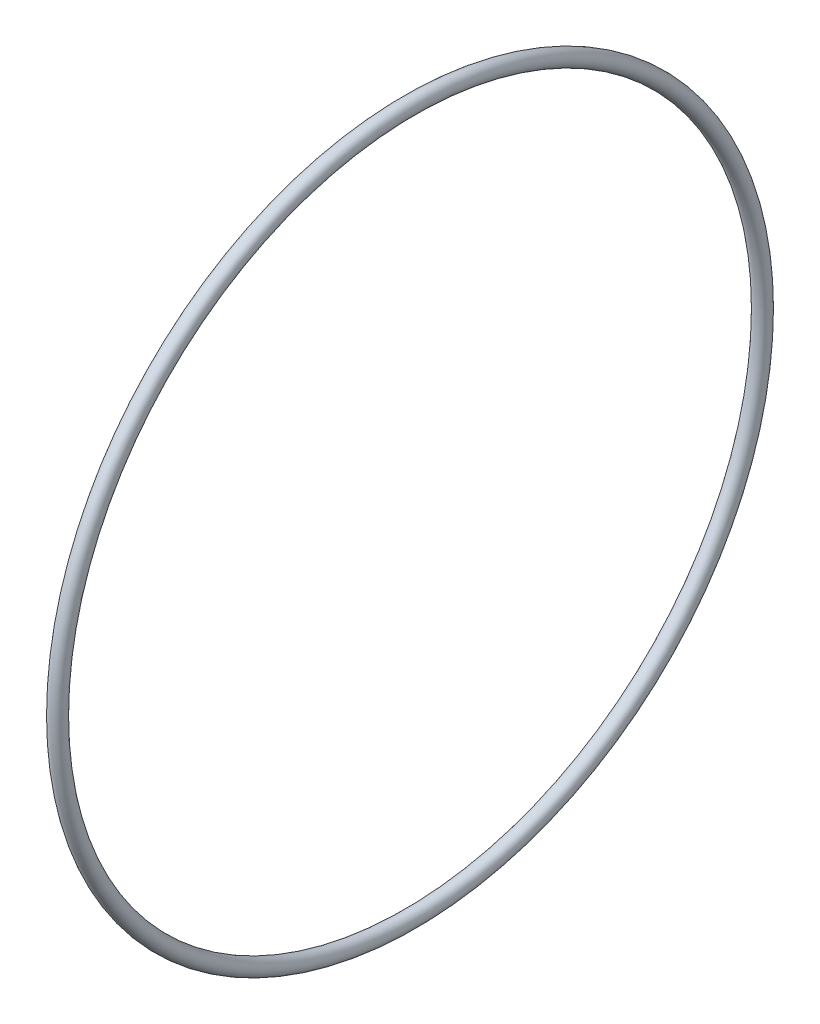
SolidWorks part; units mm, degrees
material "未指定"
ref_plane "正面" through (0, 0, 0) normal (0, 0, 1) x (1, 0, 0)
ref_plane "平面" through (0, 0, 0) normal (0, 1, 0) x (1, 0, 0)
ref_plane "右側面" through (0, 0, 0) normal (1, 0, 0) x (0, 0, -1)
sketch "ｽｹｯﾁ1" plane through (0, 0, 0) normal (0, 0, 1) x (1, 0, 0)
  line L0 (0, 0) -> (10, 0) construction
  circle A0 centre (0, 70.05) radius 1.55
  dimension "D2" = 3.1
  dimension "D1" = 70.05
revolve "Oリング" add sketch "ｽｹｯﾁ1" angle 360 about L0
equation "\"GROOVE_D\" = 137"
equation "\"ORING_W\" = 3.1"
equation "\"D1@ｽｹｯﾁ1\" = (\"GROOVE_D\" + \"ORING_W\") / 2"
equation "\"D2@ｽｹｯﾁ1\" = \"ORING_W\""
